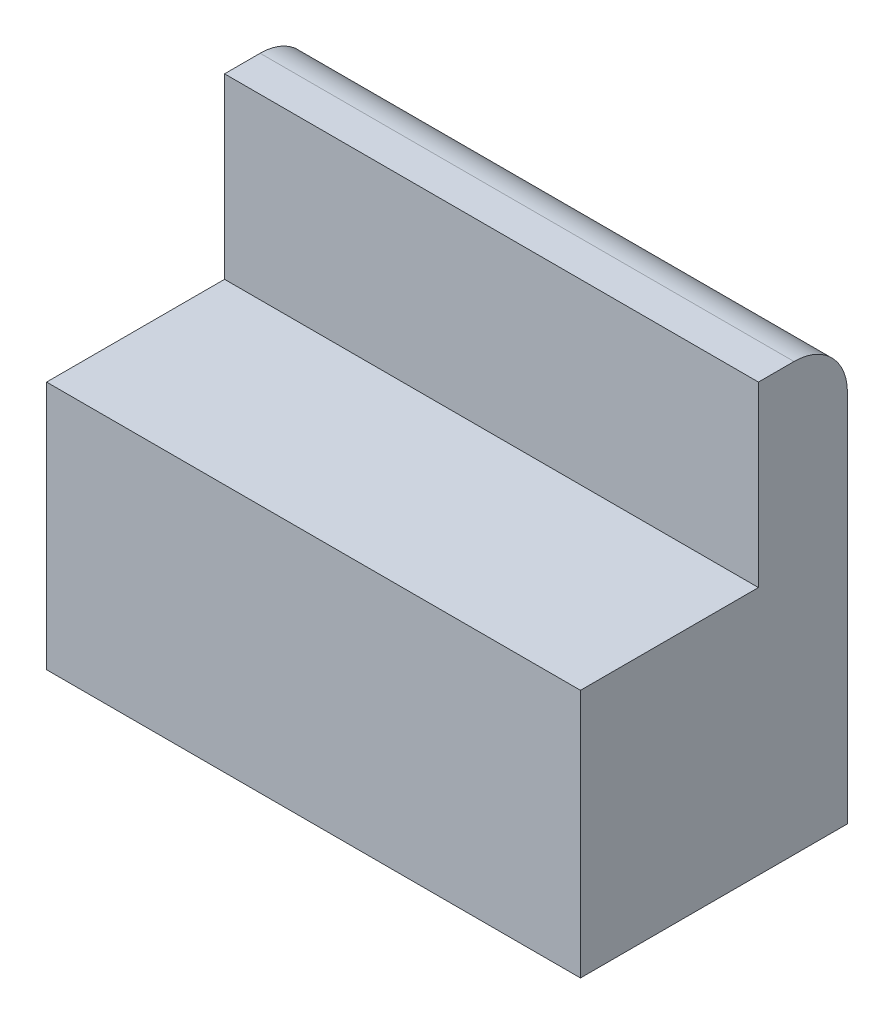
SolidWorks part; units mm, degrees
ref_plane "前视基准面" through (0, 0, 0) normal (0, 0, 1) x (1, 0, 0)
ref_plane "上视基准面" through (0, 0, 0) normal (0, 1, 0) x (1, 0, 0)
ref_plane "右视基准面" through (0, 0, 0) normal (1, 0, 0) x (0, 0, -1)
sketch "草图1" plane through (0, 0, 0) normal (0, 0, 1) x (1, 0, 0)
  line L1 (-25.3465, 20.4857) -> (4.6535, 20.4857)
  line L2 (-25.3465, 20.4857) -> (-25.3465, -3.5143)
  line L3 (-25.3465, -3.5143) -> (4.6535, -3.5143)
  line L4 (4.6535, 20.4857) -> (4.6535, -3.5143)
  dimension "D1" = 30
  dimension "D2" = 24
extrude "凸台-拉伸1" add sketch "草图1" along normal blind 15
sketch "草图2" plane through (0, 0, 15) normal (0, 0, 1) x (1, 0, 0)
  line L0 (4.6535, -3.5143) -> (4.6535, 20.4857) construction
  line L1 (-25.3465, 20.4857) -> (4.6535, 20.4857)
  line L2 (-25.3465, 20.4857) -> (-25.3465, 10.4857)
  line L3 (-25.3465, 10.4857) -> (4.6535, 10.4857)
  line L4 (4.6535, 20.4857) -> (4.6535, 10.4857)
  line L5 (-25.3465, -3.5143) -> (4.6535, -3.5143) construction
  dimension "D1" = 14
extrude "切除-拉伸1" cut sketch "草图2" against normal blind 10
fillet "圆角1" radius 3 1 edges at (-10.3465, 20.4857, 0)
